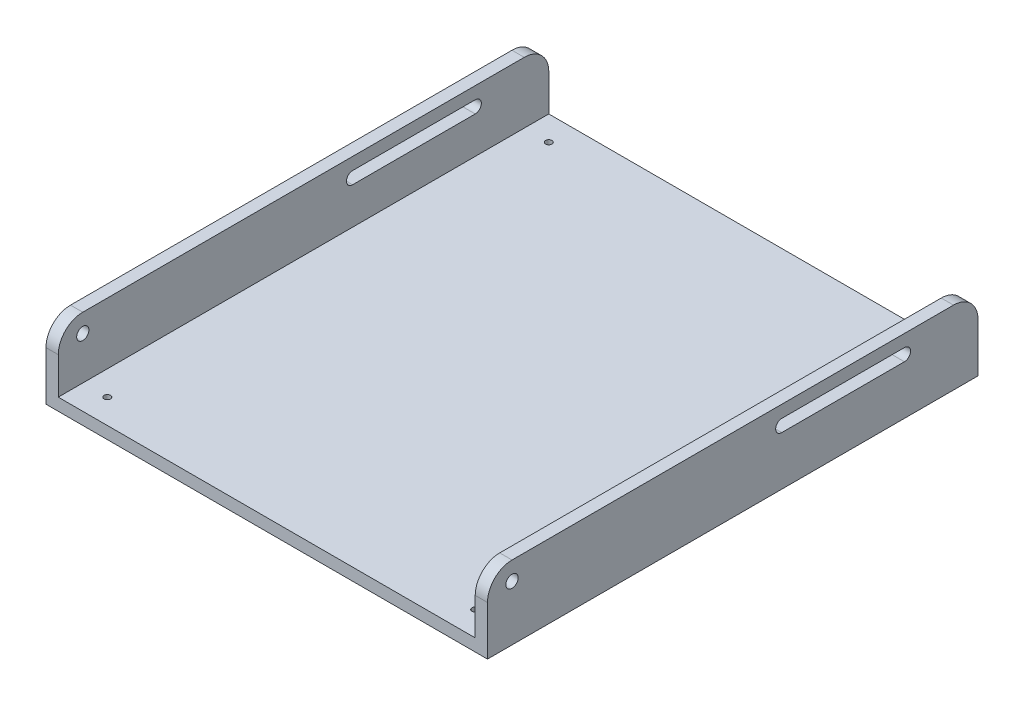
SolidWorks part; units mm, degrees
material "PVC 0.007 Plasticized"
ref_plane "Front Plane" through (0, 0, 0) normal (0, 0, 1) x (1, 0, 0)
ref_plane "Top Plane" through (0, 0, 0) normal (0, 1, 0) x (1, 0, 0)
ref_plane "Right Plane" through (0, 0, 0) normal (1, 0, 0) x (0, 0, -1)
sketch "Sketch1" plane through (0, 0, 0) normal (0, 0, 1) x (1, 0, 0)
  line L0 (-150, 0) -> (210, 0)
  line L1 (210, 0) -> (210, 60)
  line L2 (-150, 0) -> (-150, 60)
  dimension "D1" = 360
  dimension "D2" = 60
  dimension "D3" = 60
  dimension "D4" = 150
extrude "Extrude-Thin1" add sketch "Sketch1" along normal mid plane 400 thin thin type one direction wall 10
sketch "Sketch2" plane through (210, 0, 0) normal (1, 0, 0) x (0, 0, -1)
  line L0 (40, 45) -> (140, 45) construction
  line L1 (40, 50) -> (140, 50)
  line L2 (40, 40) -> (140, 40)
  line L3 (-200, 0) -> (200, 0) construction
  line L4 (200, 60) -> (200, 0) construction
  arc A0 (40, 50) -> (40, 40) centre (40, 45) ccw
  arc A1 (140, 40) -> (140, 50) centre (140, 45) ccw
  point P2 (90, 45)
  dimension "D1" = 45
  dimension "D2" = 10
  dimension "D3" = 100
  dimension "D4" = 60
extrude "Cut-Extrude1" cut sketch "Sketch2" against normal blind 364
sketch "Sketch3" plane through (-150, 0, 0) normal (-1, 0, 0) x (0, 0, 1)
  line L0 (200, 0) -> (200, 60) construction
  line L1 (200, 0) -> (-200, 0) construction
  circle A0 centre (180, 45) radius 5
  dimension "D1" = 10
  dimension "D2" = 20
  dimension "D3" = 45
extrude "Cut-Extrude2" cut sketch "Sketch3" against normal through all
fillet "Radyus1" radius 20 4 edges at (205, 60, 200) (-145, 60, 200) (-145, 60, -200) (205, 60, -200)
sketch "Çizim1" plane through (0, 10, 0) normal (0, 1, 0) x (1, 0, 0)
  line L0 (200, 200) -> (-140, 200) construction
  line L1 (-140, -200) -> (-140, 200) construction
  line L2 (200, -200) -> (200, 200) construction
  point P0 (-120, 180)
  point P1 (180, 180)
  point P2 (180, -180)
  point P3 (-120, -180)
  dimension "D1" = 20
  dimension "D2" = 20
  dimension "D3" = 20
  dimension "D4" = 20
  dimension "D5" = 20
hole_wizard "M5 Helisarmal için Zıvana matkabı1" positions "3B Çizim1" profile "Çizim2" hole size "M5x0.8" standard "ANSI Metrik"
sketch3d "3B Çizim1"
  point P0 (-120, 10, 180)
  point P3 (180, 10, 180)
  point P6 (180, 10, -180)
  point P9 (-120, 10, -180)
sketch "Çizim2" plane through (-120, 10, 180) normal (1, 0, 0) x (0, 0, 1)
  line L0 (0, 0) -> (0, 13.5622)
  line L1 (0, 13.5622) -> (2.6, 12)
  line L2 (2.6, 12) -> (2.6, 0)
  line L5 (2.6, 0) -> (0, 0)
  line L10 (0, 13.5622) -> (-2.6, 12) construction
  line L11 (0, -6.35) -> (0, 107.95) construction
  dimension "Hole Dia." = 5.2
  dimension "Hole Depth" = 12
  dimension "Drill Angle" = 118
